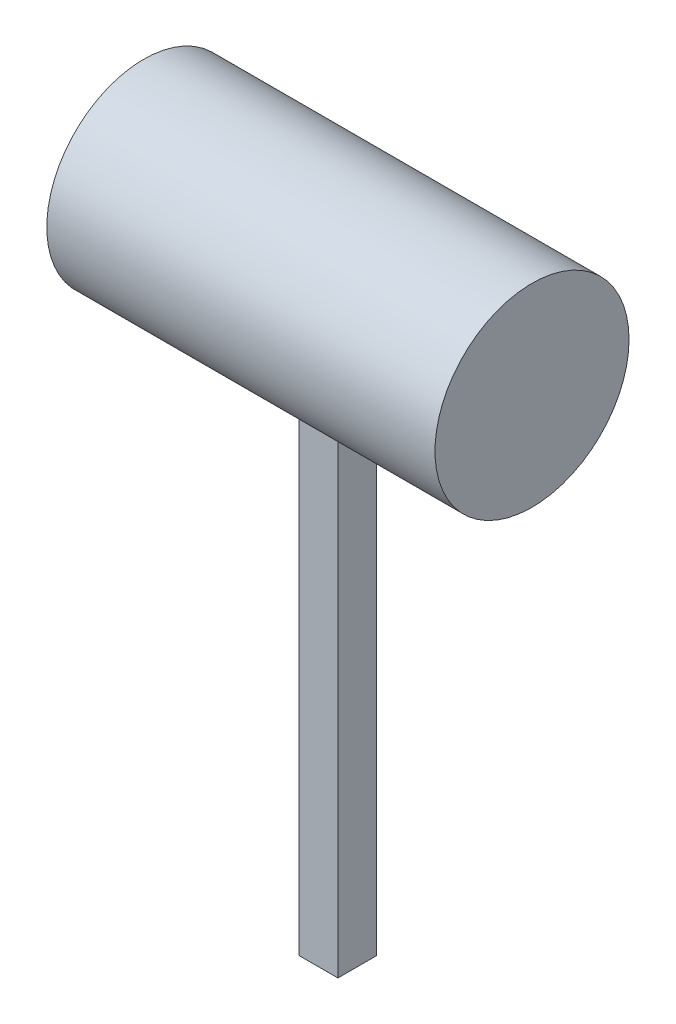
SolidWorks part; units mm, degrees
ref_plane "Front Plane" through (0, 0, 0) normal (0, 0, 1) x (1, 0, 0)
ref_plane "Top Plane" through (0, 0, 0) normal (0, 1, 0) x (1, 0, 0)
ref_plane "Right Plane" through (0, 0, 0) normal (1, 0, 0) x (0, 0, -1)
sketch "Sketch1" plane through (0, 0, 0) normal (1, 0, 0) x (0, 0, -1)
  circle A0 centre (0, 0) radius 5
  dimension "D1" = 10
extrude "Boss-Extrude1" add sketch "Sketch1" along normal mid plane 20
sketch "Sketch2" plane through (0, 0, 0) normal (0, 0, 1) x (1, 0, 0)
  line L1 (-1, 0) -> (1, 0)
  line L2 (-1, 0) -> (-1, -30)
  line L3 (-1, -30) -> (1, -30)
  line L4 (1, 0) -> (1, -30)
  point P4 (0, 0)
  point P5 (0, 0)
  dimension "D1" = 2
  dimension "D2" = 30
extrude "Boss-Extrude2" add sketch "Sketch2" along normal mid plane 2
